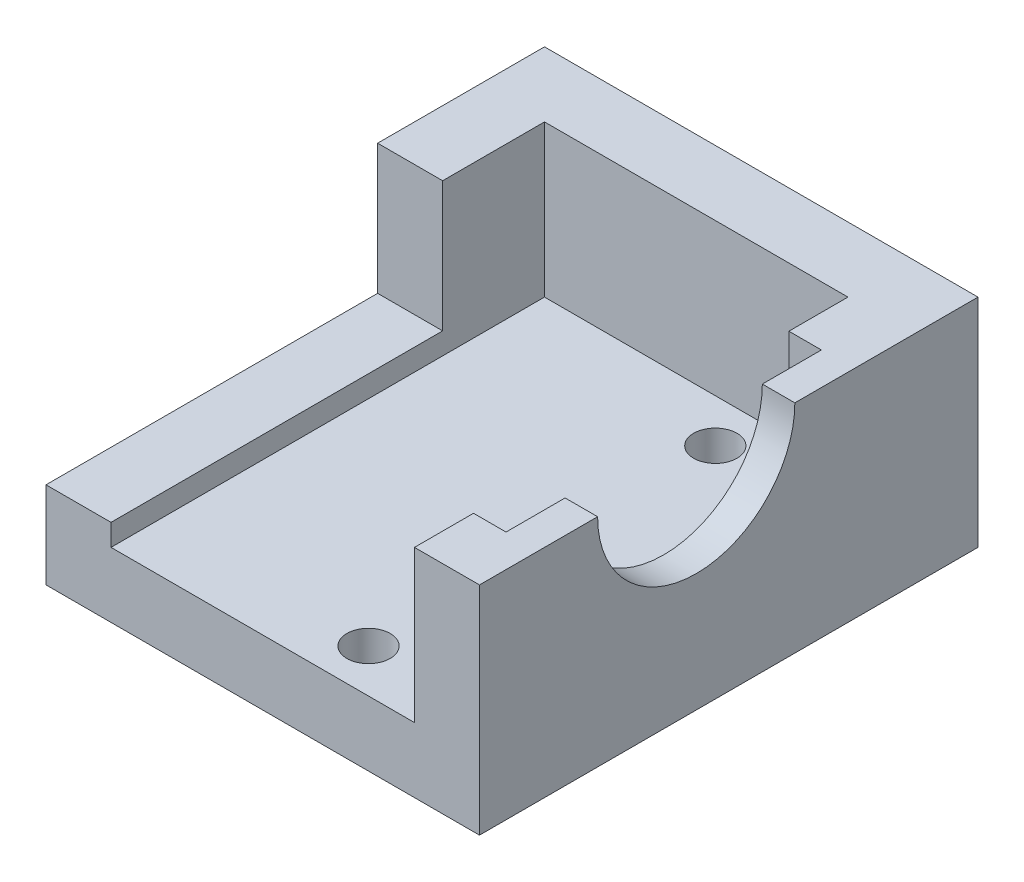
SolidWorks part; units mm, degrees
material "ABS"
ref_plane "Front Plane" through (0, 0, 0) normal (0, 0, 1) x (1, 0, 0)
ref_plane "Top Plane" through (0, 0, 0) normal (0, 1, 0) x (1, 0, 0)
ref_plane "Right Plane" through (0, 0, 0) normal (1, 0, 0) x (0, 0, -1)
sketch "Sketch1" plane through (0, 0, 0) normal (0, 1, 0) x (1, 0, 0)
  line L1 (10, -11.5) -> (-10, -11.5)
  line L2 (10, -11.5) -> (10, 11.5)
  line L3 (10, 11.5) -> (-10, 11.5)
  line L4 (-10, -11.5) -> (-10, 11.5)
  line L5 (10, -11.5) -> (-10, 11.5) construction
  line L6 (10, 11.5) -> (-10, -11.5) construction
  point P0 (0, 0)
  dimension "D1" = 20
  dimension "D2" = 23
extrude "Boss-Extrude1" add sketch "Sketch1" along normal blind 10
sketch "Sketch3" plane through (0, 10, 0) normal (0, 1, 0) x (1, 0, 0)
  line L0 (0, -11.5) -> (-7, -11.5)
  line L1 (-10, -11.5) -> (10, -11.5) construction
  line L2 (0, -11.5) -> (7, -11.5)
  line L3 (-7, -11.5) -> (-7, 8.5)
  line L4 (-7, 8.5) -> (7, 8.5)
  line L5 (7, 8.5) -> (7, -11.5)
  dimension "D1" = 7
  dimension "D2" = 7
  dimension "D3" = 20
extrude "Cut-Extrude1" cut sketch "Sketch3" against normal blind 7
sketch "Sketch4" plane through (10, 0, 0) normal (1, 0, 0) x (0, 0, -1)
  line L0 (-11.5, 10) -> (-1.5, 10) construction
  line L3 (-11.5, 10) -> (11.5, 10) construction
  circle A1 centre (-1.5, 10) radius 4.55
  dimension "D1" = 10
  dimension "D2" = 9.1
extrude "Cut-Extrude6" cut sketch "Sketch4" against normal blind 7
sketch "Sketch9" plane through (7, 0, 0) normal (-1, 0, 0) x (0, 0, 1)
  line L0 (6.05, 10) -> (8.775, 10) construction
  line L1 (11.5, 10) -> (6.05, 10) construction
  line L2 (-3.05, 10) -> (-5.775, 10) construction
  line L3 (-3.05, 10) -> (-8.5, 10) construction
  line L4 (11.5, 3) -> (-8.5, 3) construction
  line L5 (-5.775, 10) -> (8.775, 10)
  line L6 (-5.775, 10) -> (-5.775, 3)
  line L7 (-5.775, 3) -> (8.775, 3)
  line L8 (8.775, 10) -> (8.775, 3)
extrude "Cut-Extrude8" cut sketch "Sketch9" against normal blind 1.5
sketch "Sketch10" plane through (-10, 0, 0) normal (-1, 0, 0) x (0, 0, 1)
  line L1 (11.5, 10) -> (-3.8, 10)
  line L2 (11.5, 10) -> (11.5, 4)
  line L3 (11.5, 4) -> (-3.8, 4)
  line L4 (-3.8, 10) -> (-3.8, 4)
  dimension "D1" = 6
  dimension "D2" = 15.3
extrude "Cut-Extrude9" cut sketch "Sketch10" against normal blind 5.5
sketch "Sketch11" plane through (0, 0, 0) normal (0, -1, 0) x (1, 0, 0)
  line L0 (10, 11.5) -> (2.88, 11.5) construction
  line L1 (-10, 11.5) -> (10, 11.5) construction
  line L2 (2.88, 11.5) -> (2.88, 9.5) construction
  line L3 (2.88, 9.5) -> (2.88, -6.5) construction
  circle A0 centre (2.88, 9.5) radius 1
  circle A1 centre (2.88, -6.5) radius 1
  dimension "D3" = 2
  dimension "D5" = 2
  dimension "D1" = 7.12
  dimension "D2" = 2
  dimension "D4" = 16
extrude "Cut-Extrude10" cut sketch "Sketch11" against normal blind 5.5
